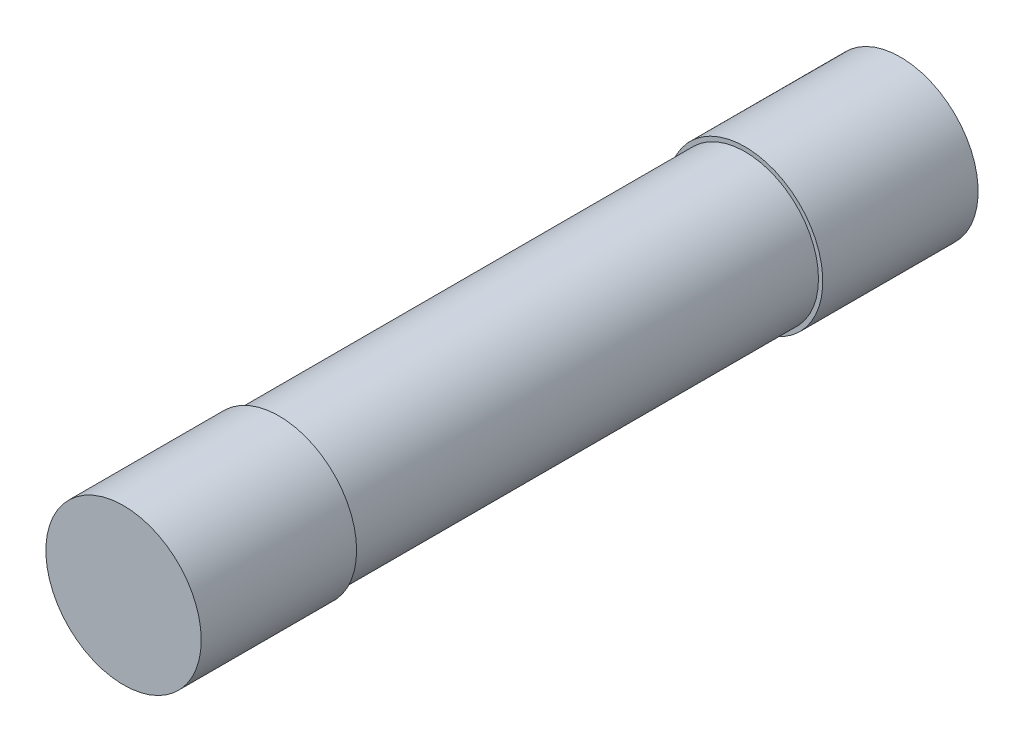
SolidWorks part; units mm, degrees
material "Brass"
ref_plane "Ground_Plane" through (0, 0, 0) normal (0, 0, 1) x (1, 0, 0)
ref_plane "VehicleCentre_Plane" through (0, 0, 0) normal (0, 1, 0) x (1, 0, 0)
ref_plane "FrontAxle_Plane" through (0, 0, 0) normal (1, 0, 0) x (0, 0, -1)
sketch "Sketch1" plane through (0, 0, 0) normal (0, 0, 1) x (1, 0, 0)
  circle A0 centre (0, 0) radius 3.175
  dimension "D1" = 6.35
extrude "Boss-Extrude1" add sketch "Sketch1" along normal blind 6.35
sketch "Sketch2" plane through (0, 0, 0) normal (0, 0, -1) x (-1, 0, 0)
  circle A0 centre (0, 0) radius 3
  dimension "D1" = 6
extrude "Boss-Extrude2" add sketch "Sketch2" along normal blind 19.05 separate body
sketch "Sketch3" plane through (0, 0, -19.05) normal (0, 0, -1) x (-1, 0, 0)
  circle A0 centre (0, 0) radius 3.175 construction
  circle A1 centre (0, 0) radius 3.175
extrude "Boss-Extrude3" add sketch "Sketch3" along normal blind 6.35 separate body
